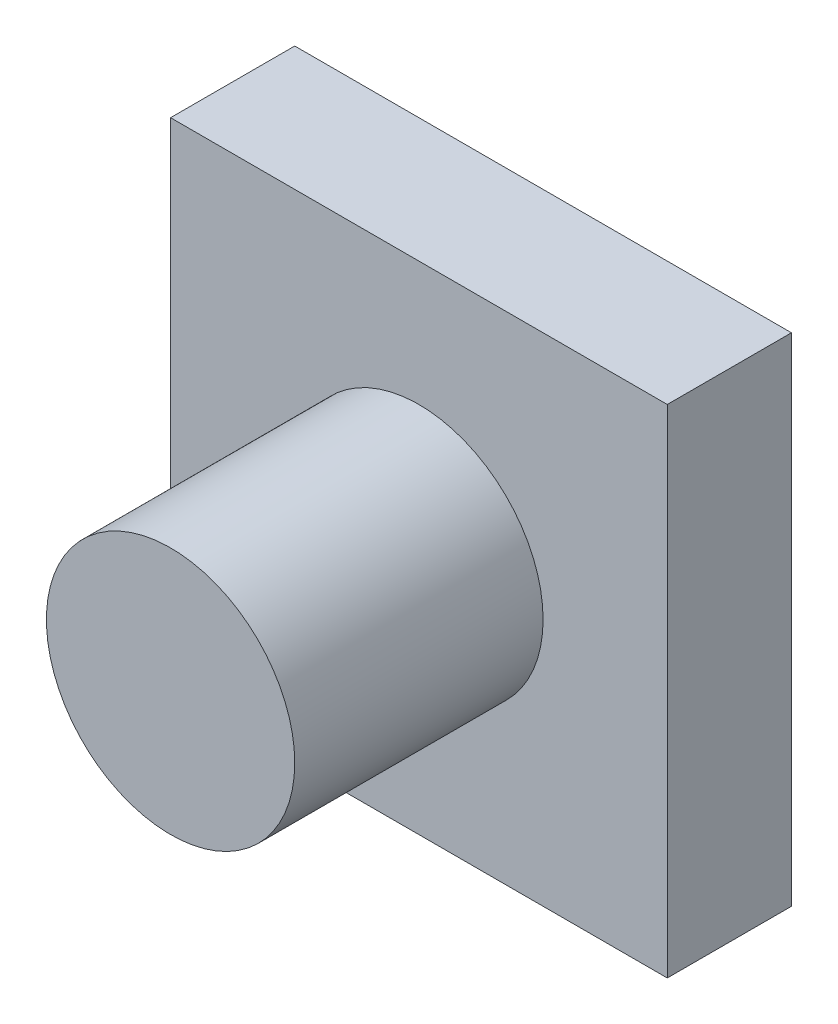
SolidWorks part; units mm, degrees
material "1.0503 (C45)"
ref_plane "Front Plane" through (0, 0, 0) normal (0, 0, 1) x (1, 0, 0)
ref_plane "Top Plane" through (0, 0, 0) normal (0, 1, 0) x (1, 0, 0)
ref_plane "Right Plane" through (0, 0, 0) normal (1, 0, 0) x (0, 0, -1)
sketch "Esquisse1" plane through (0, 0, 0) normal (0, 0, 1) x (1, 0, 0)
  line L1 (-20, -20) -> (20, -20)
  line L2 (-20, -20) -> (-20, 20)
  line L3 (-20, 20) -> (20, 20)
  line L4 (20, -20) -> (20, 20)
  line L5 (-20, -20) -> (20, 20) construction
  line L6 (-20, 20) -> (20, -20) construction
  point P0 (0, 0)
  dimension "D1" = 40
extrude "Boss.-Extru.3" add sketch "Esquisse1" along normal blind 10 contours L2 L3 L4 L1
sketch "Esquisse2" plane through (0, 0, 10) normal (0, 0, 1) x (1, 0, 0)
  circle A0 centre (0, 0) radius 10
  dimension "D1" = 20
extrude "Boss.-Extru.4" add sketch "Esquisse2" along normal blind 20
